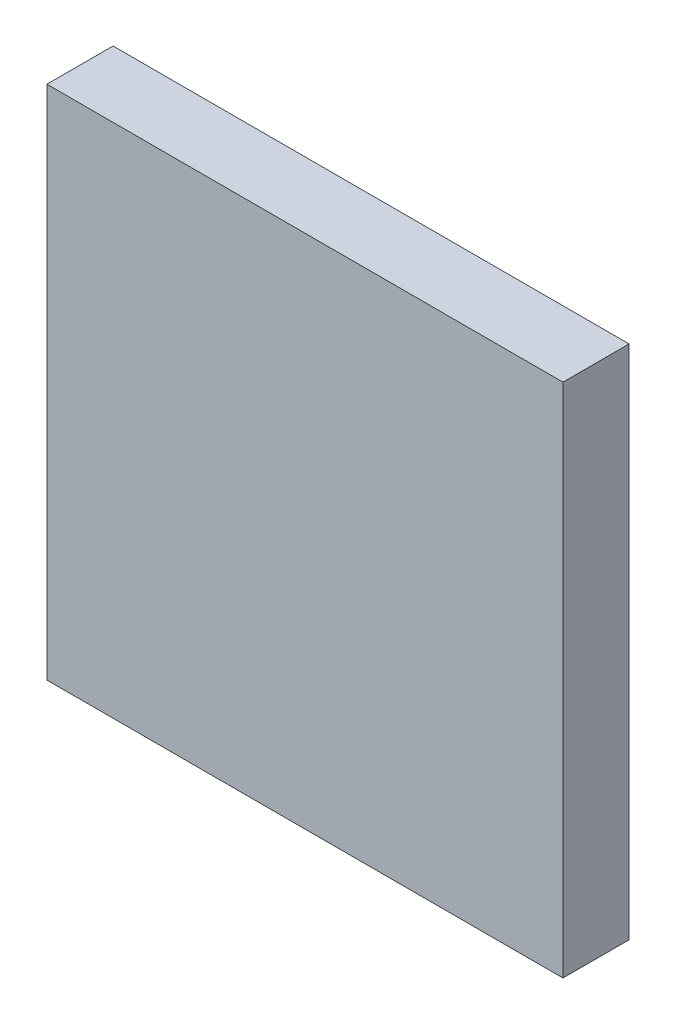
SolidWorks part; units mm, degrees
ref_plane "Front Plane" through (0, 0, 0) normal (0, 0, 1) x (1, 0, 0)
ref_plane "Top Plane" through (0, 0, 0) normal (0, 1, 0) x (1, 0, 0)
ref_plane "Right Plane" through (0, 0, 0) normal (1, 0, 0) x (0, 0, -1)
sketch "Sketch1" plane through (0, 0, 0) normal (0, 0, 1) x (1, 0, 0)
  line L1 (0, 0) -> (39, 0)
  line L2 (0, 0) -> (0, 39)
  line L3 (0, 39) -> (39, 39)
  line L4 (39, 0) -> (39, 39)
extrude "Boss-Extrude1" add sketch "Sketch1" along normal blind 5
